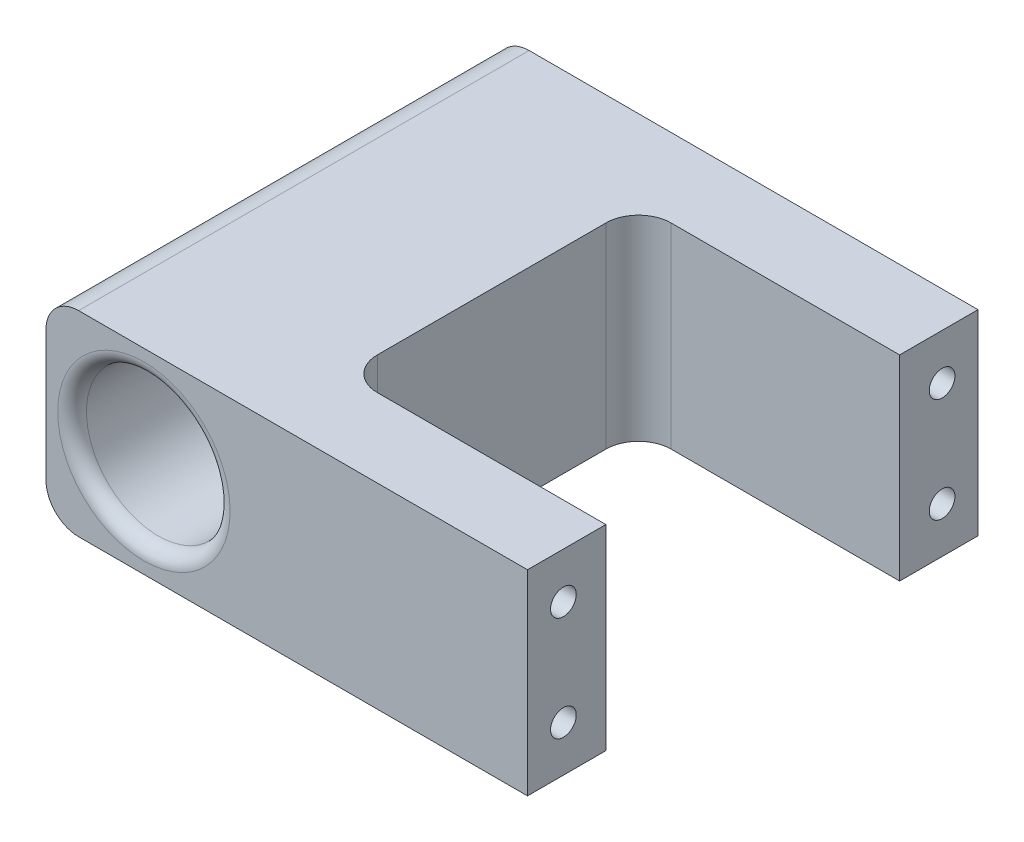
SolidWorks part; units mm, degrees
material "6061 Alloy"
ref_plane "Front Plane" through (0, 0, 0) normal (0, 0, 1) x (1, 0, 0)
ref_plane "Top Plane" through (0, 0, 0) normal (0, 1, 0) x (1, 0, 0)
ref_plane "Right Plane" through (0, 0, 0) normal (1, 0, 0) x (0, 0, -1)
sketch "Sketch1" plane through (0, 0, 0) normal (0, 0, 1) x (1, 0, 0)
  line L0 (0, 19.05) -> (74.61, 19.05)
  line L1 (0, 19.05) -> (-19.05, 19.05)
  line L2 (0, -55) -> (0, 55) construction
  line L3 (74.61, 19.05) -> (74.61, -19.05)
  line L4 (74.61, -19.05) -> (0, -19.05)
  line L5 (48.895, 0) -> (-48.895, 0) construction
  line L6 (-19.05, 19.05) -> (-19.05, -19.05)
  line L7 (-19.05, -19.05) -> (0, -19.05)
  circle A1 centre (0, 0) radius 13.97
  point P6 (74.61, 0)
  dimension "D3" = 27.94
  dimension "D1" = 38.1
  dimension "D2" = 74.61
extrude "Boss-Extrude1" add sketch "Sketch1" along normal blind 87.63 contours L4 L0 L3
fillet "Fillet3" radius 2.794 2 edges at (13.97, 0, 0) (13.97, 0, 87.63)
sketch "Sketch2" plane through (74.61, 0, 0) normal (1, 0, 0) x (0, 0, -1)
  line L0 (-43.815, 19.05) -> (-43.815, -19.05)
  line L1 (-87.63, 19.05) -> (0, 19.05) construction
  line L2 (-87.63, -19.05) -> (0, -19.05) construction
  line L3 (-43.815, 0) -> (-88.265, 0)
  line L4 (48.895, 0) -> (-48.895, 0) construction
  line L5 (-43.815, 0) -> (0.635, 0)
  line L6 (-88.265, 0) -> (-80.645, 0)
  line L7 (-80.645, 0) -> (-80.645, 10.16)
  line L8 (-80.645, 0) -> (-80.645, -10.16)
  line L9 (0.635, 0) -> (-6.985, 0)
  line L10 (-6.985, 0) -> (-6.985, 10.16)
  line L11 (-6.985, 0) -> (-6.985, -10.16)
  point P14 (-80.645, 10.16)
  point P15 (-80.645, -10.16)
  point P17 (-6.985, 10.16)
  point P18 (-6.985, -10.16)
  point P19 (-80.645, 10.16)
  point P21 (-80.645, -10.16)
  point P23 (-81.0221, 9.179)
  point P24 (0, 0)
  point P25 (0, 0)
  point P26 (0, 0)
  point P27 (0, 0)
  dimension "D1" = 88.9
  dimension "D2" = 7.62
  dimension "D3" = 7.62
  dimension "D4" = 10.16
hole_wizard "M6x1.0 Tapped Hole1" positions "Sketch2" profile "Sketch15" tap size "M6x1.0" standard "ANSI Metric"
sketch "Sketch15" plane through (74.61, -10.16, 80.645) normal (0, 1, 0) x (0, 0, -1)
  line L0 (0, 0) -> (0, 42.6502)
  line L1 (0, 42.6502) -> (2.5, 41.148)
  line L2 (2.5, 41.148) -> (2.5, 0)
  line L5 (2.5, 0) -> (0, 0)
  line L10 (0, 42.6502) -> (-2.5, 41.148) construction
  line L11 (0, -6.35) -> (0, 107.95) construction
  dimension "Tap Drill Dia." = 5
  dimension "Tap Drill Depth" = 41.148
  dimension "Drill Angle" = 118
sketch "Sketch16" plane through (74.61, 0, 0) normal (1, 0, 0) x (0, 0, -1)
  line L0 (-15.24, 19.05) -> (-15.24, -19.05)
  line L1 (-87.63, 19.05) -> (0, 19.05) construction
  line L2 (-87.63, -19.05) -> (0, -19.05) construction
  line L3 (-15.24, -19.05) -> (-72.39, -19.05)
  line L4 (-72.39, -19.05) -> (-72.39, 19.05)
  line L5 (-72.39, 19.05) -> (-43.815, 19.05)
  line L6 (-43.815, 19.05) -> (-15.24, 19.05)
  dimension "D1" = 57.15
extrude "Cut-Extrude1" cut sketch "Sketch16" against normal blind 50.8 contours L6 L0 L3 L4 L5
fillet "Fillet4" radius 6.35 2 edges at (23.81, 0, 15.24) (23.81, 0, 72.39)
fillet "Fillet5" radius 6.35 2 edges at (-19.05, -19.05, 43.815) (-19.05, 19.05, 43.815)
equation "\"rodmountsides\"= 1.5in"
equation "\"rodmountheight\"= \"plateheight\" - \"rodmountheighttolerance\"'plateheight+tolerance"
equation "\"hipplatetogearboxdiff\"= 2in"
equation "\"screwholeheightoffset\"= 0.3in"
equation "\"screwholewidthoffset\"= 0.35in"
equation "\"gearboxfacetorodmiddlediff\"= 23.81mm"
equation "\"D1@Sketch1\"=\"rodmountsides\""
equation "\"D2@Sketch1\"=\"gearboxfacetorodmiddlediff\"+\"hipplatetogearboxdiff\""
equation "\"roddiameter\"= 1in"
equation "\"rodholetolerance\"= 0.05in"
equation "\"D3@Sketch1\"=\"roddiameter\"+2*(\"rodholetolerance\")"
equation "\"D1@Boss-Extrude1\"=\"rodmountheight\""
equation "\"filetradius\"= 0.1in'filet of the rod"
equation "\"filettolerance\"= 0.01in'same as above"
equation "\"filet\"= \"filetradius\" + \"filettolerance\""
equation "\"D1@Fillet3\"=\"filet\""
equation "\"rodmountheighttolerance\"= 0.05in"
equation "\"plateheight\"= 3.5in"
equation "\"D3@Sketch2\"=\"screwholeheightoffset\""
equation "\"D4@Sketch2\"=(\"rodmountsides\"/2)-\"screwholewidthoffset\""
